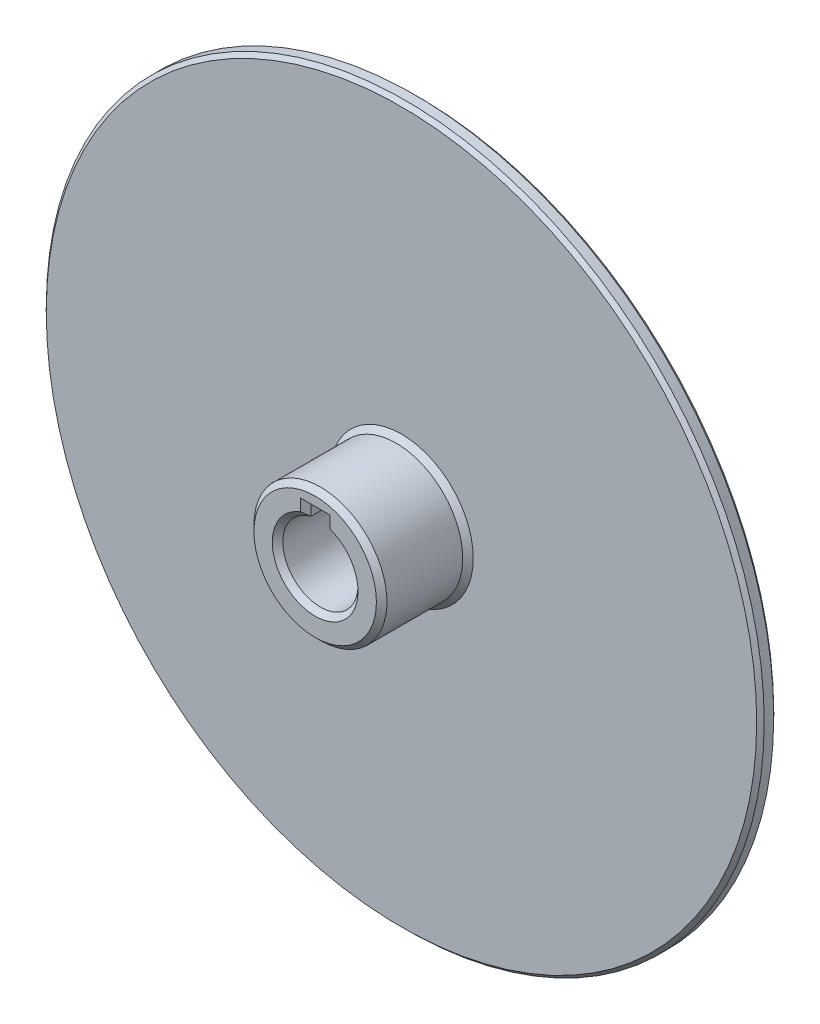
SolidWorks part; units mm, degrees
ref_plane "Front Plane" through (0, 0, 0) normal (0, 0, 1) x (1, 0, 0)
ref_plane "Top Plane" through (0, 0, 0) normal (0, 1, 0) x (1, 0, 0)
ref_plane "Right Plane" through (0, 0, 0) normal (1, 0, 0) x (0, 0, -1)
sketch "Sketch1" plane through (0, 0, 0) normal (0, 0, 1) x (1, 0, 0)
  circle A0 centre (0, 0) radius 121.3315
  dimension "D1" = 242.663
extrude "Boss-Extrude1" add sketch "Sketch1" along normal blind 5.7658
sketch "Sketch2" plane through (0, 0, 5.7658) normal (0, 0, 1) x (1, 0, 0)
  circle A0 centre (0, 0) radius 22.479
  dimension "D1" = 44.958
extrude "Boss-Extrude2" add sketch "Sketch2" along normal blind 29.1749
sketch "Sketch3" plane through (0, 0, 34.9407) normal (0, 0, 1) x (1, 0, 0)
  circle A0 centre (0, 0) radius 12.7
  dimension "D1" = 25.4
extrude "Cut-Extrude1" cut sketch "Sketch3" against normal through all both and the other way through all
sketch "Sketch4" plane through (0, 0, 34.9407) normal (0, 0, 1) x (1, 0, 0)
  line L1 (-3.175, 15.875) -> (3.175, 15.875)
  line L2 (-3.175, 15.875) -> (-3.175, 9.525)
  line L3 (-3.175, 9.525) -> (3.175, 9.525)
  line L4 (3.175, 15.875) -> (3.175, 9.525)
  line L5 (-3.175, 15.875) -> (3.175, 9.525) construction
  line L6 (-3.175, 9.525) -> (3.175, 15.875) construction
  circle A0 centre (0, 0) radius 12.7 construction
  point P0 (0, 12.7)
  dimension "D1" = 6.35
  dimension "D2" = 6.35
extrude "Cut-Extrude2" cut sketch "Sketch4" against normal through all both and the other way through all
chamfer "Chamfer1" distance 1.27 angle 45 2 edges at (121.3315, 0, 0) (121.3315, 0, 5.7658)
chamfer "Chamfer2" distance 1.778 angle 45 10 edges at (3.175, 14.0859, 0) (0, -12.7, 0) (-3.175, 14.0859, 0) (0, 15.875, 0) (3.175, 14.0859, 34.9407) (0, 15.875, 34.9407) (-3.175, 14.0859, 34.9407) (0, -12.7, 34.9407) (22.479, 0, 5.7658) (22.479, 0, 34.9407)
